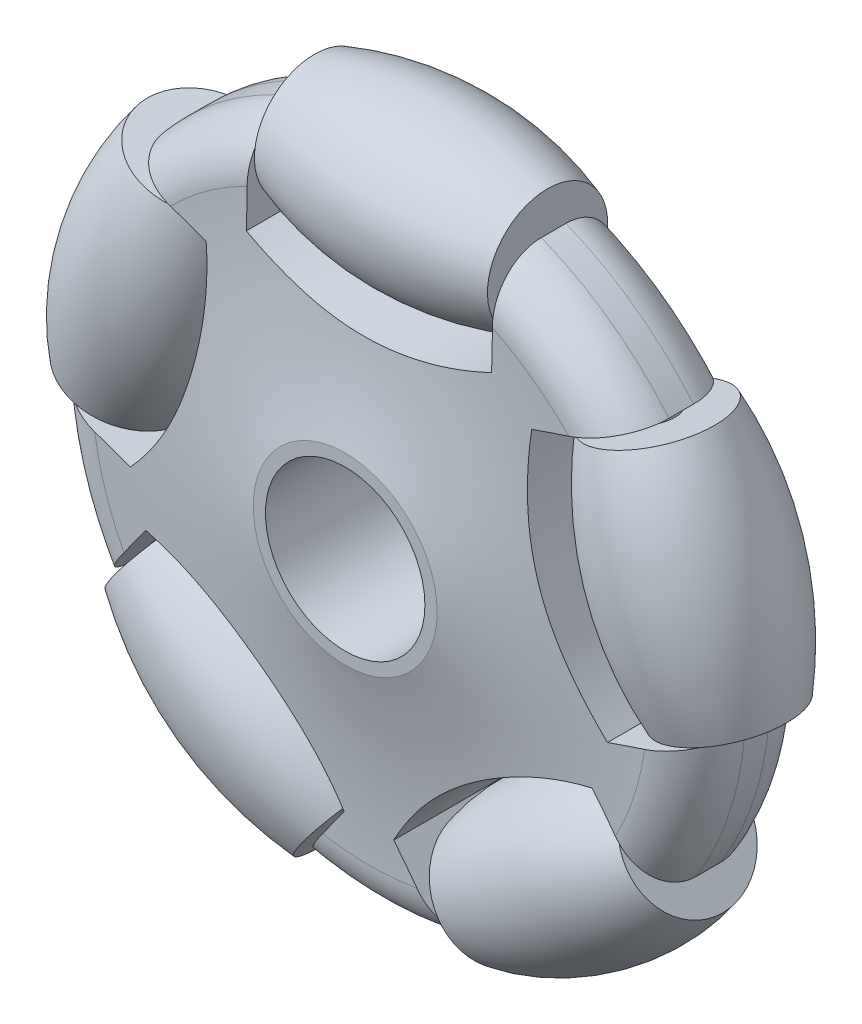
SolidWorks part; units mm, degrees
ref_plane "Front Plane" through (0, 0, 0) normal (0, 0, 1) x (1, 0, 0)
ref_plane "Top Plane" through (0, 0, 0) normal (0, 1, 0) x (1, 0, 0)
ref_plane "Right Plane" through (0, 0, 0) normal (1, 0, 0) x (0, 0, -1)
sketch "Sketch1" plane through (0, 0, 0) normal (1, 0, 0) x (0, 0, -1)
  line L0 (-5, 0) -> (5, 0) construction
  line L1 (0, 0) -> (0, 26.65) construction
  line L2 (-1, 26.65) -> (1, 26.65)
  line L8 (5, 22.65) -> (5, 6.5) construction
  line L10 (-5, 22.65) -> (-5, 6.5) construction
  line L11 (-7, 6.5) -> (6, 6.5)
  line L12 (-7, 6.5) -> (-7, 7.5)
  line L13 (6, 6.5) -> (6, 7.5)
  arc A0 (-5, 22.65) -> (-1, 26.65) centre (-1, 22.65) cw
  arc A2 (5, 22.65) -> (1, 26.65) centre (1, 22.65) ccw
  arc A3 (-7, 7.5) -> (-5, 22.65) centre (-63.3806, 22.65) ccw
  arc A4 (6, 7.5) -> (5, 22.65) centre (120.2613, 22.65) cw
  point P3 (0, 0)
  point P8 (-5, 22.65)
  point P9 (-1, 26.65)
  point P21 (0, 6.5)
  dimension "D1" = 10
  dimension "D2" = 26.65
  dimension "D3" = 4
  dimension "D4" = 2
  dimension "D5" = 1
  dimension "D6" = 1
  dimension "D7" = 1
  dimension "D8" = 6.5
revolve "Revolve1" add sketch "Sketch1" angle 360 about L0
sketch "Sketch2" plane through (0, 0, 0) normal (0, 0, 1) x (1, 0, 0)
  line L0 (0, 0) -> (0, 26.65) construction
  line L1 (10, 24.7027) -> (10, 17.2027)
  line L2 (-10, 24.7027) -> (-10, 17.2027)
  line L3 (26.5838, -1.877) -> (19.4509, -4.1946)
  line L4 (20.4035, 17.1441) -> (13.2706, 14.8265)
  line L5 (6.4297, -25.8627) -> (2.0213, -19.7951)
  line L6 (22.61, -14.107) -> (18.2017, -8.0394)
  line L7 (-22.61, -14.107) -> (-18.2017, -8.0394)
  line L8 (-6.4297, -25.8627) -> (-2.0213, -19.7951)
  line L9 (-20.4035, 17.1441) -> (-13.2706, 14.8265)
  line L10 (-26.5838, -1.877) -> (-19.4509, -4.1946)
  circle A0 centre (0, 0) radius 26.65 construction
  arc A1 (10, 17.2027) -> (-10, 17.2027) centre (0, 38.83) cw
  arc A2 (19.4509, -4.1946) -> (13.2706, 14.8265) centre (36.9295, 11.9991) cw
  arc A3 (2.0213, -19.7951) -> (18.2017, -8.0394) centre (22.8237, -31.4141) cw
  arc A4 (-18.2017, -8.0394) -> (-2.0213, -19.7951) centre (-22.8237, -31.4141) cw
  arc A5 (-13.2706, 14.8265) -> (-19.4509, -4.1946) centre (-36.9295, 11.9991) cw
  arc A6 (10, 24.7027) -> (-10, 24.7027) centre (0, 0) ccw
  arc A7 (-20.4035, 17.1441) -> (-26.5838, -1.877) centre (0, 0) ccw
  arc A8 (-22.61, -14.107) -> (-6.4297, -25.8627) centre (0, 0) ccw
  arc A9 (6.4297, -25.8627) -> (22.61, -14.107) centre (0, 0) ccw
  arc A10 (26.5838, -1.877) -> (20.4035, 17.1441) centre (0, 0) ccw
  point P12 (0, 15.0027)
  point P34 (0, 0)
  dimension "D1" = 10
  dimension "D2" = 7.5
  dimension "D3" = 5
  dimension "D4" = 2.2
extrude "Cut-Extrude1" cut sketch "Sketch2" against normal through all both and the other way through all
sketch "Sketch3" plane through (0, 0, 0) normal (0, 0, 1) x (1, 0, 0)
  line L0 (9.5, 27.3998) -> (9.5, 24)
  line L1 (10, 24.7027) -> (10, 20.323) construction
  line L2 (0, 0) -> (0, 29) construction
  line L3 (0, 22.5) -> (10, 22.5) construction
  line L4 (10, 22.5) -> (10, 24)
  line L5 (10, 24) -> (9.5, 24)
  line L6 (-9.5, 27.3998) -> (-9.5, 24)
  line L7 (-10, 24) -> (-9.5, 24)
  line L8 (-10, 22.5) -> (-10, 24)
  line L9 (10, 22.5) -> (-10, 22.5)
  arc A0 (9.5, 27.3998) -> (-9.5, 27.3998) centre (0, 0) ccw
  point P8 (0, 22.5)
  dimension "D1" = 58
  dimension "D2" = 0.5
  dimension "D4" = 1.5
revolve "Revolve2" add sketch "Sketch3" angle 360 about L9
pattern_circular "CirPattern1" count 5 over 360 about axis through (0, 0, 0) along (0, 0, 1) of "Revolve2"
